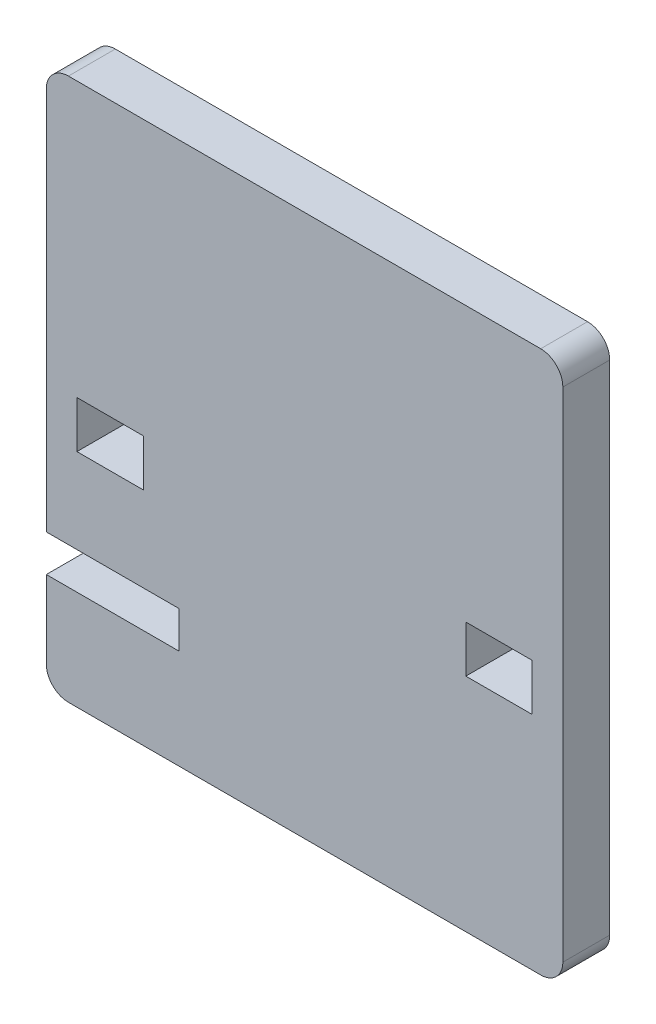
SolidWorks part; units mm, degrees
ref_plane "Front Plane" through (0, 0, 0) normal (0, 0, 1) x (1, 0, 0)
ref_plane "Top Plane" through (0, 0, 0) normal (0, 1, 0) x (1, 0, 0)
ref_plane "Right Plane" through (0, 0, 0) normal (1, 0, 0) x (0, 0, -1)
sketch "Sketch1" plane through (0, 0, 0) normal (0, 0, 1) x (1, 0, 0)
  line L0 (0, 36.75) -> (0, -36.75) construction
  line L1 (-35, 36.75) -> (35, 36.75)
  line L2 (-35, 36.75) -> (-35, -36.75)
  line L3 (-35, -36.75) -> (35, -36.75)
  line L4 (35, 36.75) -> (35, -36.75)
  line L5 (-35, 36.75) -> (35, -36.75) construction
  line L6 (-35, -36.75) -> (35, 36.75) construction
  line L13 (-35, 0) -> (35, 0) construction
  point P0 (0, 0)
  dimension "D1" = 70
  dimension "D2" = 73.5
extrude "Boss-Extrude1" add sketch "Sketch1" along normal blind 6.35
sketch "Sketch2" plane through (0, 0, 6.35) normal (0, 0, 1) x (1, 0, 0)
  line L0 (-17.008, -23.25) -> (-17.008, -42.577) construction
  line L1 (-30.85, -0.4) -> (-21.85, -0.4)
  line L2 (-30.85, -0.4) -> (-30.85, -6.75)
  line L3 (-30.85, -6.75) -> (-21.85, -6.75)
  line L4 (-21.85, -0.4) -> (-21.85, -6.75)
  line L5 (-35, -18.25) -> (-17.008, -18.25)
  line L6 (0, 36.75) -> (0, -36.75) construction
  line L7 (-35, -18.25) -> (-35, -23.25)
  line L8 (-35, -23.25) -> (-17.008, -23.25)
  line L9 (-17.008, -18.25) -> (-17.008, -23.25)
  line L10 (-35, -36.75) -> (35, -36.75) construction
  line L11 (0, -1.6689) -> (0, -10.4) construction
  line L12 (21.85, -0.4) -> (21.85, -6.75)
  line L13 (30.85, -6.75) -> (21.85, -6.75)
  line L14 (30.85, -0.4) -> (30.85, -6.75)
  line L15 (30.85, -0.4) -> (21.85, -0.4)
  line L16 (-35, -18.25) -> (-17.008, -23.25) construction
  line L17 (-35, -23.25) -> (-17.008, -18.25) construction
  line L18 (-35, 36.75) -> (-35, -36.75) construction
  line L19 (-17.008, -33.25) -> (-6.6892, -33.25) construction
  line L20 (-17.008, -33.25) -> (-17.008, -39.6) construction
  line L21 (-17.008, -39.6) -> (-6.6892, -39.6) construction
  line L22 (-6.6892, -33.25) -> (-6.6892, -39.6) construction
  point P15 (-26.004, -20.75)
  dimension "D1" = 21.85
  dimension "D2" = 9
  dimension "D3" = 6.35
  dimension "D4" = 30
  dimension "D5" = 14
  dimension "D6" = 17.992
  dimension "D7" = 5
  dimension "D8" = 6.35
  dimension "D9" = 10
  dimension "D10" = 10.3187
extrude "Cut-Extrude1" cut sketch "Sketch2" against normal blind 6.35
fillet "Fillet1" radius 3 4 edges at (-35, -36.75, 3.175) (35, -36.75, 3.175) (35, 36.75, 3.175) (-35, 36.75, 3.175)
